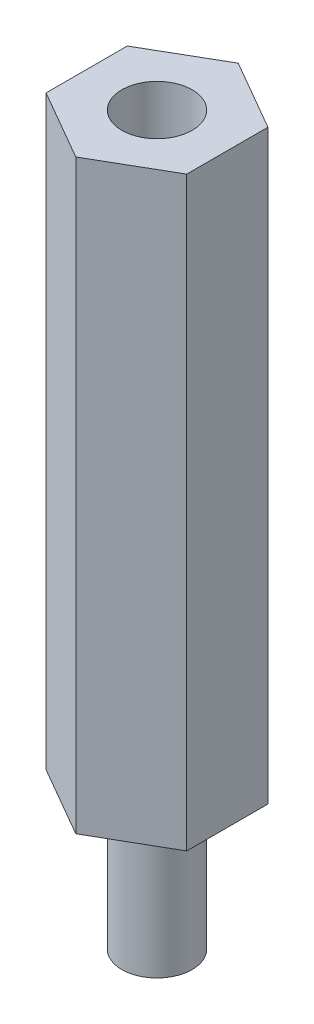
SolidWorks part; units mm, degrees
ref_plane "Front Plane" through (0, 0, 0) normal (0, 0, 1) x (1, 0, 0)
ref_plane "Top Plane" through (0, 0, 0) normal (0, 1, 0) x (1, 0, 0)
ref_plane "Right Plane" through (0, 0, 0) normal (1, 0, 0) x (0, 0, -1)
sketch "Sketch1" plane through (0, 0, 0) normal (0, 1, 0) x (1, 0, 0)
  line L1 (0, 3.4641) -> (-3, 1.7321)
  line L2 (-3, 1.7321) -> (-3, -1.7321)
  line L3 (-3, -1.7321) -> (0, -3.4641)
  line L4 (0, -3.4641) -> (3, -1.7321)
  line L5 (3, -1.7321) -> (3, 1.7321)
  line L6 (3, 1.7321) -> (0, 3.4641)
  circle A0 centre (0, 0) radius 3 construction
extrude "Boss-Extrude1" add sketch "Sketch1" along normal blind 25
sketch "Sketch2" plane through (0, 25, 0) normal (0, 1, 0) x (1, 0, 0)
  circle A0 centre (0, 0) radius 1.5
extrude "Boss-Extrude2" add sketch "Sketch2" against normal blind 31
sketch "Sketch3" plane through (0, 25, 0) normal (0, 1, 0) x (1, 0, 0)
  circle A0 centre (0, 0) radius 1.5
extrude "Cut-Extrude1" cut sketch "Sketch3" against normal blind 5
